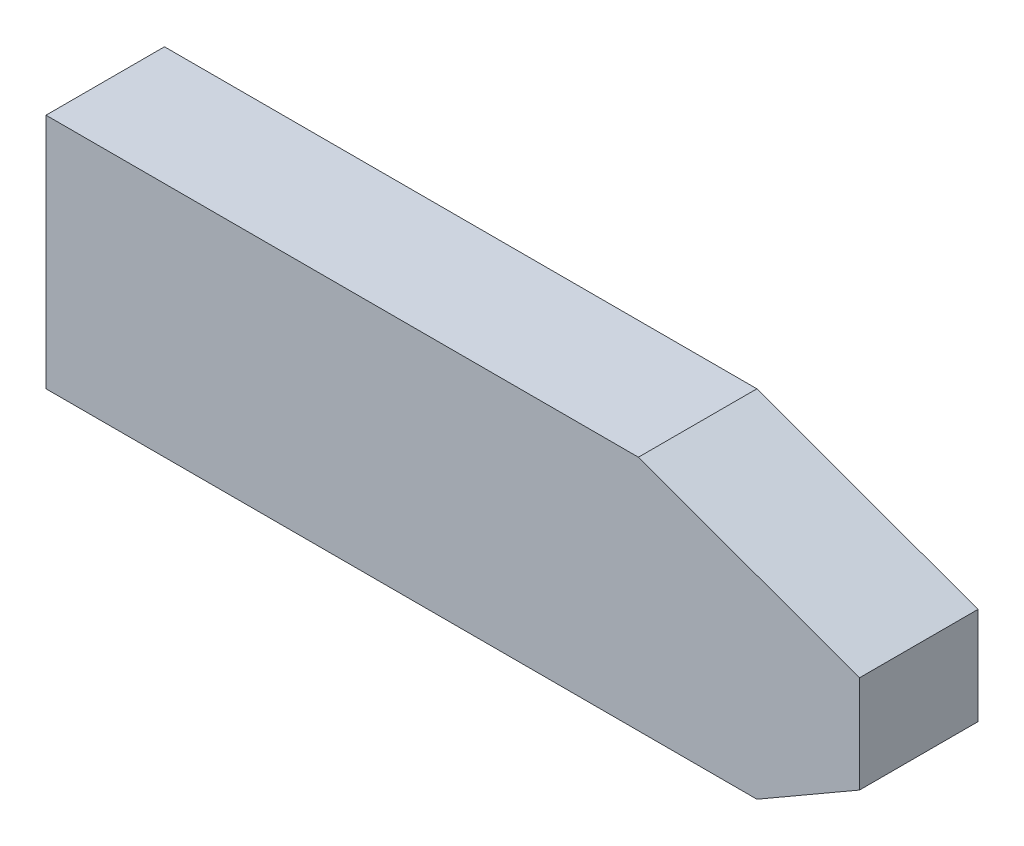
SolidWorks part; units mm, degrees
ref_plane "Front Plane" through (0, 0, 0) normal (0, 0, 1) x (1, 0, 0)
ref_plane "Top Plane" through (0, 0, 0) normal (0, 1, 0) x (1, 0, 0)
ref_plane "Right Plane" through (0, 0, 0) normal (1, 0, 0) x (0, 0, -1)
sketch "Sketch1" plane through (0, 0, 0) normal (0, 0, 1) x (1, 0, 0)
  line L0 (0, 0) -> (0, 50.8)
  line L1 (0, 50.8) -> (127, 50.8)
  line L2 (127, 50.8) -> (174.397, 33.5489)
  line L3 (174.397, 33.5489) -> (174.397, 12.7)
  line L4 (174.397, 12.7) -> (152.4, 0)
  line L5 (152.4, 0) -> (0, 0)
  dimension "D1" = 50.8
  dimension "D2" = 127
  dimension "D3" = 152.4
  dimension "D4" = 20
  dimension "D5" = 30
  dimension "D6" = 25.4
extrude "Boss-Extrude1" add sketch "Sketch1" along normal blind 25.4
